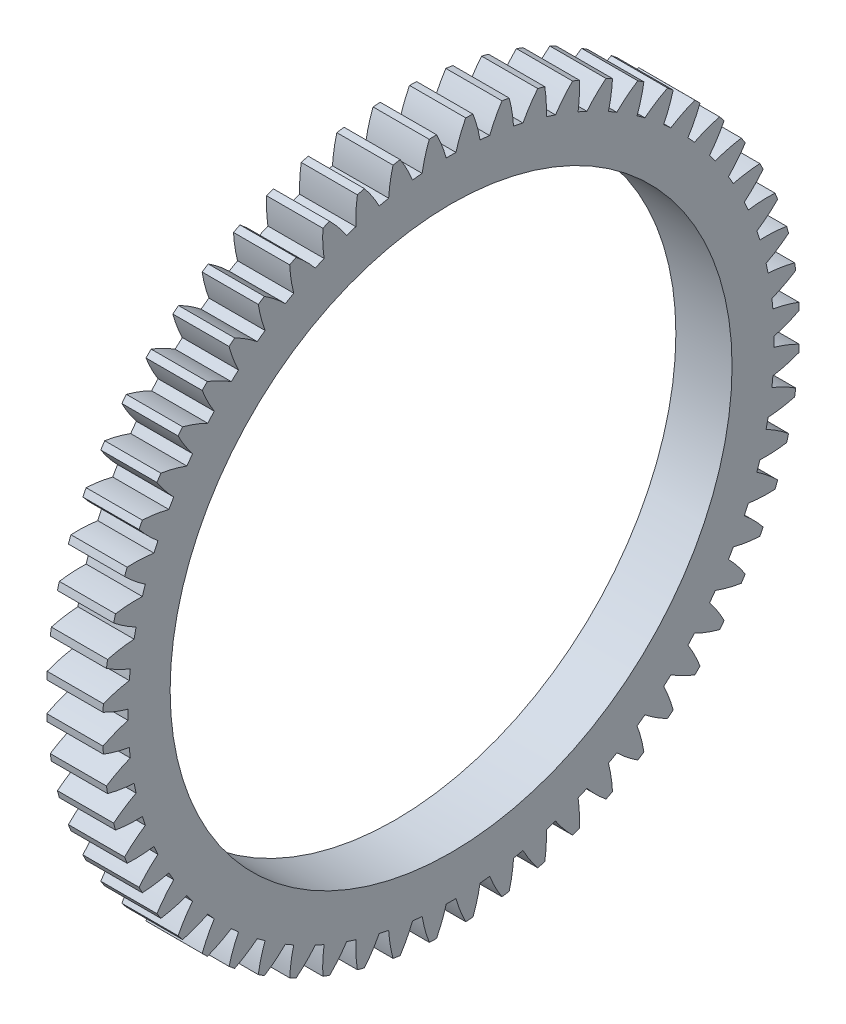
SolidWorks part; units mm, degrees
ref_plane "Plane1" through (0, 0, 0) normal (0, 0, 1) x (1, 0, 0)
ref_plane "Plane2" through (0, 0, 0) normal (0, 1, 0) x (1, 0, 0)
ref_plane "Plane3" through (0, 0, 0) normal (1, 0, 0) x (0, 0, -1)
sketch "HoldingSke" plane through (0, 0, 0) normal (0, 1, 0) x (1, 0, 0)
  line L0 (0, 0) -> (0.5, -0.866)
  line L1 (-15, 0) -> (100, 0) construction
  line L2 (0, 0) -> (-2.1039, 2.3779)
  line L3 (0, 0) -> (-11.863, 4.5341)
  line L4 (0, 0) -> (4.318, 7.479)
  line L5 (0, 0) -> (-46.8476, -17.4728)
  line L6 (0, 0) -> (-4.1448, -2.7965)
  line L7 (-2.1039, 2.3779) -> (8.6586, 51.2059)
  line L8 (-76.2, 54.61) -> (-71.9, 54.61)
  line L9 (-71.009, 38.7566) -> (-53.1078, 45.2721)
  line L10 (-76.2, 71.12) -> (104.1128, 71.12)
  line L11 (0, 0) -> (-5, 0)
  line L12 (-76.2, 101.6) -> (-76.162, 101.6)
  line L13 (24.9733, 27.94) -> (52.9518, 28.4284)
  line L14 (24.9733, 27.94) -> (24.9743, 27.94)
  line L15 (24.9733, 27.94) -> (100.4006, 29.5858)
  line L16 (-63.627, -1) -> (-12.827, -1)
  circle A0 centre (0, 0) radius 25
  circle A1 centre (0, 0) radius 28.749
  circle A2 centre (0, 0) radius 37.5
  circle A3 centre (0, 0) radius 25
  dimension "MHD" = 57.498
  dimension "Hub_dia" = 75
  dimension "Bore" = 50
  dimension "MBD" = 50
  dimension "Num_teeth" = 60
  dimension "Pitch" = 1
  dimension "Overall_len" = 50
  dimension "Show_teeth" = 60
  dimension "Thickness" = 5
  dimension "OAL" = 50.0001
  dimension "T_dim" = 4.3
  dimension "Ap" = 20
  dimension "H" = 19.05
  dimension "Pitch_radius" = 180.3128
  dimension "Width" = 5
  dimension "Backlash" = 0.038
  dimension "Addendum_fac" = 1
  dimension "Dedendum_fac" = 1.25
  dimension "Clearance_fac" = 0.25
  dimension "Dedendum_add" = 0.001
  dimension "Module" = 1
sketch "BasProSke" plane through (0, 0, 0) normal (0, 1, 0) x (1, 0, 0)
  line L0 (-10, 0) -> (60, 0) construction
  line L1 (0, 0) -> (0, 31)
  line L2 (0, 0) -> (5, 0)
  line L3 (5, 0) -> (5, 31)
  line L4 (5, 31) -> (0, 31)
  dimension "Thickness" = 5
  dimension "Diameter" = 62
revolve "Base-Revolve" add sketch "BasProSke" angle 360 about L0
sketch "TooCutSke" plane through (0, 0, 0) normal (1, 0, 0) x (0, 0, -1)
  line L1 (0, 0) -> (0, 107) construction
  line L2 (0, 0) -> (-0.8518, 29.9879) construction
  line L3 (0, 0) -> (-3.1393, 59.9006) construction
  line L4 (-0.8518, 29.9879) -> (-1.5696, 29.9503) construction
  arc A0 (0.4302, 28.7458) -> (-0.4302, 28.7458) centre (0, 0) ccw
  arc A1 (1.3127, 30.9976) -> (-1.3127, 30.9976) centre (0, 0) ccw
  circle A2 centre (0, 0) radius 30 construction
  circle A3 centre (0, 0) radius 28.1908 construction
  arc A4 (-0.4302, 28.7458) -> (-1.3127, 30.9976) centre (-11.9871, 25.5153) ccw
  arc A5 (1.3127, 30.9976) -> (0.4302, 28.7458) centre (11.9871, 25.5153) ccw
  dimension "Root_dia" = 57.498
  dimension "Overcut_dia" = 62.0508
  dimension "Pitch_dia" = 60
  dimension "Base_dia" = 56.3816
  dimension "Flank_rad" = 12
  dimension "Half_ang" = 3
  dimension "Half_CT" = 0.7188
extrude "ToothCut" cut sketch "TooCutSke" along normal through all
fillet "Breaks" [suppressed] radius 0.02
fillet "RootFillets" [suppressed] radius 0.251
pattern_circular "TeethCuts" count 60 every 6 about axis through (-10, 0, 0) along (1, 0, 0) of "ToothCut", "RootFillets", "Breaks"
sketch "HubNeaOneSke" plane through (0, 0, 0) normal (-1, 0, 0) x (0, 0, 1)
  circle A0 centre (0, 0) radius 28.749
  dimension "Diameter" = 57.498
extrude "HubNearOne" [suppressed] add sketch "HubNeaOneSke" along normal blind 45.0001
sketch "HubNeaBotSke" plane through (0, 0, 0) normal (-1, 0, 0) x (0, 0, 1)
  circle A0 centre (0, 0) radius 28.749
  dimension "Diameter" = 57.498
extrude "HubNearBoth" [suppressed] add sketch "HubNeaBotSke" along normal blind 22.5
ref_plane "FarPln" through (5, 0, 0) normal (1, 0, 0) x (0, 0, -1)
sketch "HubFarSke" plane through (5, 0, 0) normal (1, 0, 0) x (0, 0, -1)
  circle A0 centre (0, 0) radius 28.749
  dimension "Diameter" = 57.498
extrude "HubFar" [suppressed] add sketch "HubFarSke" along normal blind 22.5
sketch "BorSke" plane through (0, 0, 0) normal (1, 0, 0) x (0, 0, -1)
  circle A0 centre (0, 0) radius 25
  dimension "Diameter" = 50
extrude "Bore" cut sketch "BorSke" along normal mid plane 100.0001
sketch "KeySke" plane through (0, 0, 0) normal (1, 0, 0) x (0, 0, -1)
  line L0 (-8, 0) -> (-8, 29.3)
  line L1 (-8, 29.3) -> (8, 29.3)
  line L2 (8, 29.3) -> (8, 0)
  line L3 (0, 0) -> (0, 34) construction
  line L4 (-8, 0) -> (8, 0)
  dimension "Offset" = 29.3
  dimension "Width" = 16
extrude "Keyway" [suppressed] cut sketch "KeySke" along normal mid plane 100.0001
pattern_circular "Keyway2" [suppressed] count 2 every 90 about axis through (-10, 0, 0) along (1, 0, 0)
equation "' \"Module@HoldingSke\" = 6.35"
equation "' \"Num_teeth@HoldingSke\" = 12"
equation "' \"Ap@HoldingSke\" =  20"
equation "' \"Ap@HoldingSke\" = 20"
equation "' \"Width@HoldingSke\" = 0.5 * 25.4"
equation "' \"Hub_dia@HoldingSke\"= 1 * 25.4"
equation "' \"Hub_dia@HoldingSke\" = 1 * 25.4"
equation "' \"Overall_len@HoldingSke\" = 1.0 * 25.4"
equation "' \"Bore@HoldingSke\" = 0.75 * 25.4"
equation "' \"T_dim@HoldingSke\" = 0.1 * 25.4"
equation "' \"Width@KeySke\" = 0.25 * 25.4"
equation "' \"Show_teeth@HoldingSke\" = 13"
equation "' \"Backlash@HoldingSke\" = 0.009 * 25.4"
equation "' \"Addendum_fac@HoldingSke\" = 1.0"
equation "' \"Dedendum_fac@HoldingSke\" = 1.25"
equation "' \"Dedendum_add@HoldingSke\" = 0.00005 * 25.4"
equation "' \"Clearance_fac@HoldingSke\" = 0.25"
equation "\"Pitch@HoldingSke\" = 1 / \"Module@HoldingSke\""
equation "\"Overcut_dia@TooCutSke\" = (\"Num_teeth@HoldingSke\" + 2 * \"Addendum_fac@HoldingSke\") / \"Pitch@HoldingSke\" + 0.002 * 25.4"
equation "\"Pitch_dia@TooCutSke\" = \"Num_teeth@HoldingSke\" / \"Pitch@HoldingSke\""
equation "\"Base_dia@TooCutSke\" = \"Num_teeth@HoldingSke\" / \"Pitch@HoldingSke\" * cos((\"Ap@HoldingSke\"  * 3.14159265 / 180))"
equation "\"Root_dia@TooCutSke\" = (\"Num_teeth@HoldingSke\" + 2) / \"Pitch@HoldingSke\" - 2 * (\"Addendum_fac@HoldingSke\" + \"Dedendum_fac@HoldingSke\") / \"Pitch@HoldingSke\" - \"Dedendum_add@HoldingSke\" * 2"
equation "\"Half_ang@TooCutSke\" = 180 / \"Num_teeth@HoldingSke\""
equation "\"Half_CT@TooCutSke\" = \"Num_teeth@HoldingSke\" / \"Pitch@HoldingSke\" * sin((3.14159265 / 2 / \"Num_teeth@HoldingSke\")) / 2 - 7 * \"Backlash@HoldingSke\" / 4"
equation "\"Flank_rad@TooCutSke\" = \"Num_teeth@HoldingSke\" / \"Pitch@HoldingSke\" / 5"
equation "\"Radius@RootFillets\" = \"Clearance_fac@HoldingSke\" / \"Pitch@HoldingSke\" + \"Dedendum_add@HoldingSke\""
equation "\"Break_rad@Breaks\" = 0.02 / \"Pitch@HoldingSke\""
equation "\"Thickness@HoldingSke\" = \"Width@HoldingSke\""
equation "\"OAL@HoldingSke\" = \"Thickness@HoldingSke\""
equation "\"MHD@HoldingSke\" = (\"Num_teeth@HoldingSke\" + 2) / \"Pitch@HoldingSke\" - 2 * (\"Addendum_fac@HoldingSke\" + \"Dedendum_fac@HoldingSke\")  / \"Pitch@HoldingSke\" - \"Dedendum_add@HoldingSke\" * 2"
equation "\"MBD@HoldingSke\" = (\"Num_teeth@HoldingSke\" + 2) / \"Pitch@HoldingSke\" - 2 * (\"Addendum_fac@HoldingSke\" + \"Dedendum_fac@HoldingSke\")  / \"Pitch@HoldingSke\" - \"Dedendum_add@HoldingSke\" * 2 - 0.002 * 25.4"
equation "\"MHD@HoldingSke\" = ((sgn( \"MHD@HoldingSke\" - \"Hub_dia@HoldingSke\" )-1)*( \"MHD@HoldingSke\" - \"Hub_dia@HoldingSke\" ))/-2+ \"Hub_dia@HoldingSke\""
equation "\"MBD@HoldingSke\" = ((sgn( \"MBD@HoldingSke\" - \"Bore@HoldingSke\" )-1)*( \"MBD@HoldingSke\" - \"Bore@HoldingSke\" ))/-2+ \"Bore@HoldingSke\""
equation "\"OAL@HoldingSke\" = ((sgn( \"OAL@HoldingSke\" - \"Overall_len@HoldingSke\" )+1)*( \"OAL@HoldingSke\" - \"Overall_len@HoldingSke\" ))/2 + \"Overall_len@HoldingSke\" + 0.000002 * 25.4"
equation "\"Num_teeth@TeethCuts\" = int( \"Show_teeth@HoldingSke\" ) + 1"
equation "\"Num_teeth@TeethCuts\" = ((sgn( \"Num_teeth@TeethCuts\" - \"Num_teeth@HoldingSke\" )-1)*( \"Num_teeth@TeethCuts\" - \"Num_teeth@HoldingSke\" ))/-2+ \"Num_teeth@HoldingSke\""
equation "\"Num_teeth@TeethCuts\" = ((sgn( \"Num_teeth@TeethCuts\" - 2.0)+1)*( \"Num_teeth@TeethCuts\" - 2.0))/2 +2.0"
equation "\"Angle@TeethCuts\" = 360.0 / \"Num_teeth@HoldingSke\""
equation "\"Diameter@BasProSke\" = (\"Num_teeth@HoldingSke\" + 2 * \"Addendum_fac@HoldingSke\") / \"Pitch@HoldingSke\""
equation "\"Thickness@BasProSke\"  = \"Thickness@HoldingSke\""
equation "' \"Fillet_rad@BasProSke\" =  \"Thickness@HoldingSke\" * 0.05"
equation "' \"Fillet_rad@BasProSke\" = \"Thickness@HoldingSke\" * 0.05"
equation "\"MHD@HoldingSke\" = ((sgn( \"MHD@HoldingSke\" - \"Root_dia@TooCutSke\" )-1)*( \"MHD@HoldingSke\" - \"Root_dia@TooCutSke\" ))/-2+ \"Root_dia@TooCutSke\""
equation "\"Diameter@HubNeaOneSke\" = \"MHD@HoldingSke\""
equation "\"Length@HubNearOne\" = \"OAL@HoldingSke\" - \"Thickness@BasProSke\""
equation "\"Diameter@HubNeaBotSke\" = \"MHD@HoldingSke\""
equation "\"Length@HubNearBoth\" = ( \"OAL@HoldingSke\" - \"Thickness@BasProSke\" ) / 2.0"
equation "\"Thickness@FarPln\" = \"Thickness@BasProSke\""
equation "\"Diameter@HubFarSke\" = \"MHD@HoldingSke\""
equation "\"Length@HubFar\" = ( \"OAL@HoldingSke\" - \"Thickness@BasProSke\" ) / 2.0"
equation "\"Diameter@BorSke\" = \"MBD@HoldingSke\""
equation "\"D1@Bore\" = \"OAL@HoldingSke\" * 2.0"
equation "\"D1@Keyway\" = \"OAL@HoldingSke\" * 2.0"
equation "\"Offset@KeySke\" = \"T_dim@HoldingSke\" + \"MBD@HoldingSke\" / 2.0"
